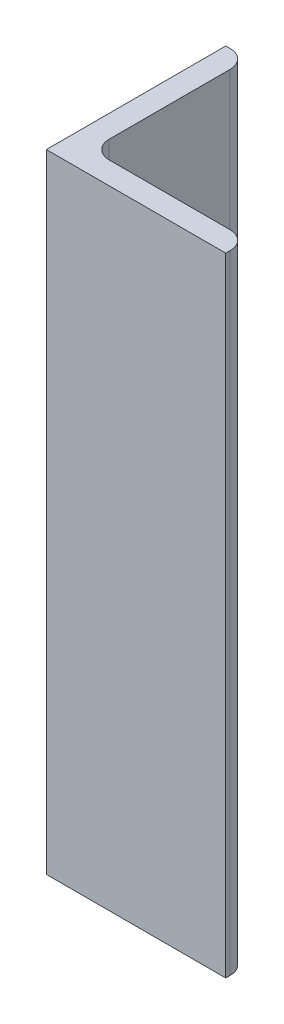
SolidWorks part; units mm, degrees
ref_plane "Front Plane" through (0, 0, 0) normal (0, 0, 1) x (1, 0, 0)
ref_plane "Top Plane" through (0, 0, 0) normal (0, 1, 0) x (1, 0, 0)
ref_plane "Right Plane" through (0, 0, 0) normal (1, 0, 0) x (0, 0, -1)
sketch "Sketch1" plane through (0, 0, 0) normal (0, 1, 0) x (1, 0, 0)
  line L0 (0, 0) -> (0, 25.4)
  line L1 (0, 25.4) -> (0.635, 25.4)
  line L2 (3.175, 22.86) -> (3.175, 5.715)
  line L3 (5.715, 3.175) -> (22.86, 3.175)
  line L4 (25.4, 0.635) -> (25.4, 0)
  line L5 (25.4, 0) -> (0, 0)
  arc A0 (22.86, 3.175) -> (25.4, 0.635) centre (22.86, 0.635) cw
  arc A1 (3.175, 5.715) -> (5.715, 3.175) centre (5.715, 5.715) ccw
  arc A2 (0.635, 25.4) -> (3.175, 22.86) centre (0.635, 22.86) cw
  point P9 (25.4, 3.175)
  dimension "D3" = 2.54
  dimension "D1" = 3.175
  dimension "D2" = 25.4
extrude "Boss-Extrude1" add sketch "Sketch1" along normal blind 88.9
